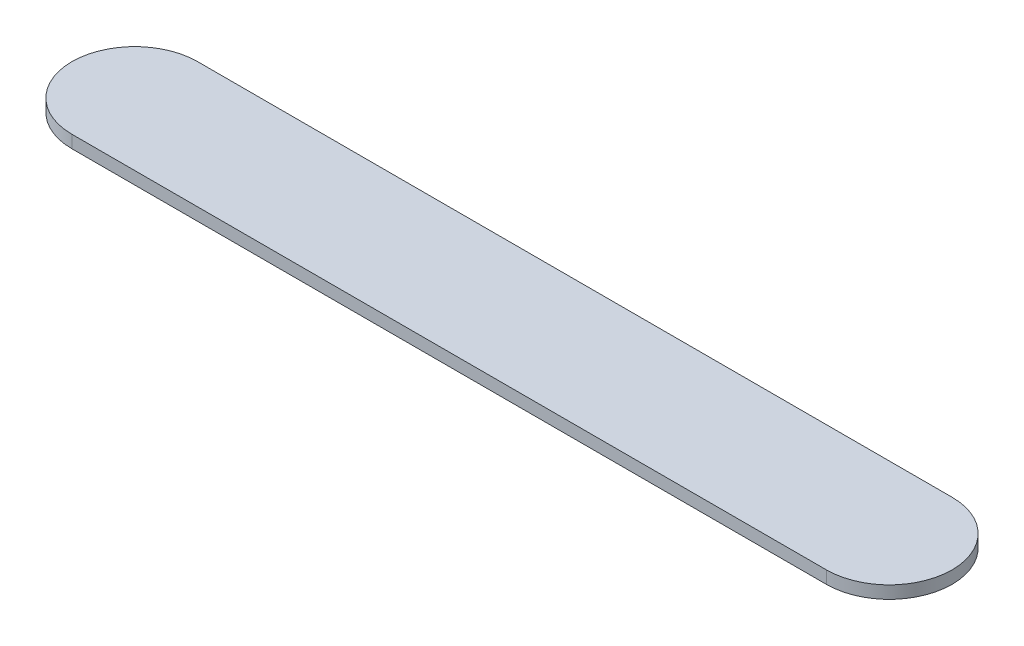
SolidWorks part; units mm, degrees
ref_plane "Front Plane" through (0, 0, 0) normal (0, 0, 1) x (1, 0, 0)
ref_plane "Top Plane" through (0, 0, 0) normal (0, 1, 0) x (1, 0, 0)
ref_plane "Right Plane" through (0, 0, 0) normal (1, 0, 0) x (0, 0, -1)
sketch "Sketch1" plane through (0, 0, 0) normal (0, 1, 0) x (1, 0, 0)
  line L0 (-47.625, 0) -> (47.625, 0) construction
  line L1 (-47.625, 7.9375) -> (47.625, 7.9375)
  line L2 (-47.625, -7.9375) -> (47.625, -7.9375)
  arc A0 (-47.625, 7.9375) -> (-47.625, -7.9375) centre (-47.625, 0) ccw
  arc A1 (47.625, -7.9375) -> (47.625, 7.9375) centre (47.625, 0) ccw
  point P3 (0, 0)
  point P8 (0, 0)
  dimension "D1" = 7.9375
  dimension "D2" = 95.25
extrude "Boss-Extrude1" add sketch "Sketch1" along normal blind 1.5875
